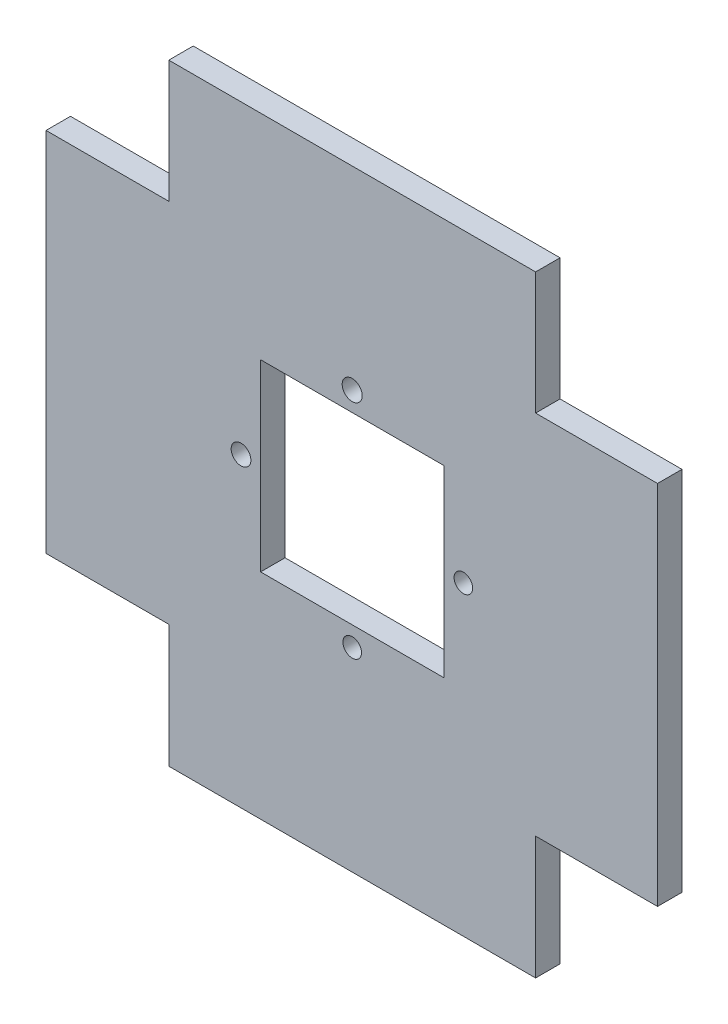
SolidWorks part; units mm, degrees
ref_plane "Front Plane" through (0, 0, 0) normal (0, 0, 1) x (1, 0, 0)
ref_plane "Top Plane" through (0, 0, 0) normal (0, 1, 0) x (1, 0, 0)
ref_plane "Right Plane" through (0, 0, 0) normal (1, 0, 0) x (0, 0, -1)
sketch "Sketch2" plane through (0, 0, 0) normal (0, 0, 1) x (1, 0, 0)
  line L1 (49.372, 30.5127) -> (-26.8113, 30.5127)
  line L2 (74.6925, 5.1222) -> (74.6925, -70.9628)
  line L3 (49.372, -96.4873) -> (-26.8113, -96.4873)
  line L4 (-52.3075, 5.1222) -> (-52.3075, -70.9628)
  line L5 (-7.7448, -13.8368) -> (30.3055, -13.8368)
  line L6 (-7.7448, -13.8368) -> (-7.7448, -52.0038)
  line L7 (74.6925, 5.1222) -> (49.372, 5.1222)
  line L8 (49.372, 30.5127) -> (49.372, 5.1222)
  line L9 (-7.7448, -52.0038) -> (30.3055, -52.0038)
  line L10 (30.3055, -13.8368) -> (30.3055, -52.0038)
  line L11 (74.6925, -70.9628) -> (49.372, -70.9628)
  line L12 (49.372, -96.4873) -> (49.372, -70.9628)
  line L15 (-52.3075, -70.9628) -> (-26.8113, -70.9628)
  line L16 (-26.8113, -96.4873) -> (-26.8113, -70.9628)
  line L19 (-52.3075, 5.1222) -> (-26.8113, 5.1222)
  line L20 (-26.8113, 30.5127) -> (-26.8113, 5.1222)
  circle A0 centre (11.2804, -9.7728) radius 2.0803
  circle A1 centre (34.3695, -32.9203) radius 1.9306
  circle A2 centre (11.2804, -56.0678) radius 1.9316
  circle A3 centre (-11.8088, -32.9203) radius 2.052
  point P0 (11.2804, -32.9203)
  point P25 (11.2804, -52.0038)
  dimension "D1" = 4.064
extrude "Boss-Extrude1" add sketch "Sketch2" along normal blind 5.08
